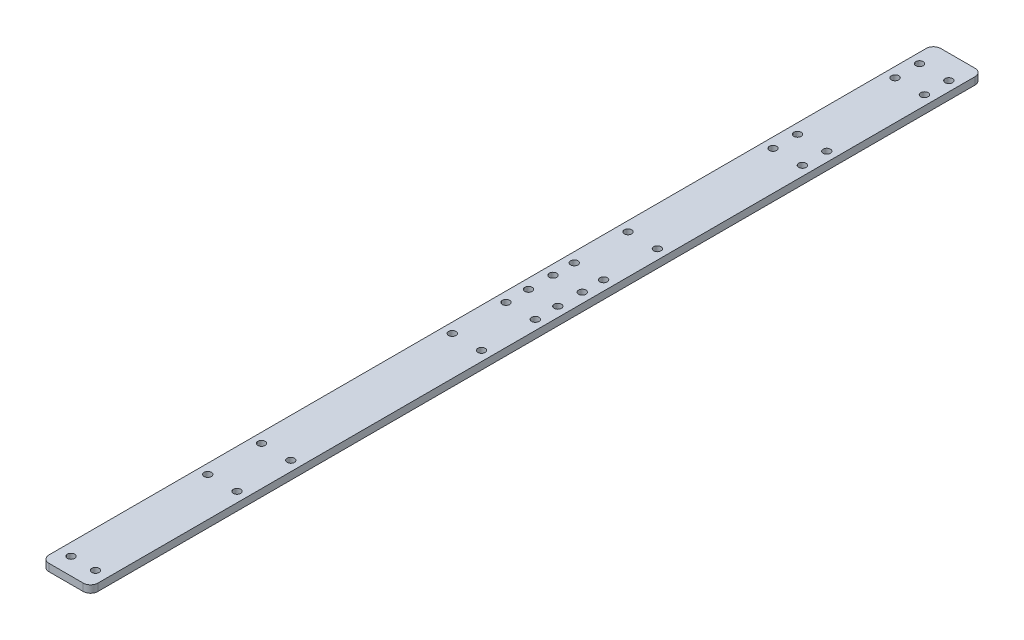
SolidWorks part; units mm, degrees
material "Thornel Mat VMA"
ref_plane "前视基准面" through (0, 0, 0) normal (0, 0, 1) x (1, 0, 0)
ref_plane "上视基准面" through (0, 0, 0) normal (0, 1, 0) x (1, 0, 0)
ref_plane "右视基准面" through (0, 0, 0) normal (1, 0, 0) x (0, 0, -1)
sketch "草图1" plane through (0, 0, 0) normal (0, 1, 0) x (1, 0, 0)
  line L0 (-9.7495, 254.1231) -> (-9.7495, -255.8769)
  line L1 (-9.7495, -255.8769) -> (10.2505, -255.8769)
  line L2 (10.2505, -255.8769) -> (10.2505, 254.1231)
  line L3 (10.2505, 254.1231) -> (-9.7495, 254.1231)
  circle A0 centre (5.2505, -103.8769) radius 1.5
  circle A1 centre (-4.7495, -103.8769) radius 1.5
  circle A2 centre (6.2134, -46.8769) radius 1.5
  circle A3 centre (-5.7866, -46.8769) radius 1.5
  circle A4 centre (6.2134, -24.8769) radius 1.5
  circle A5 centre (-5.7866, -24.8769) radius 1.5
  circle A6 centre (6.2951, 53.1231) radius 1.5
  circle A7 centre (-5.7049, 53.1231) radius 1.5
  circle A8 centre (6.2951, 75.1231) radius 1.5
  circle A9 centre (-5.7049, 75.1231) radius 1.5
  circle A10 centre (6.2634, 84.3731) radius 1.5
  circle A11 centre (-5.7366, 84.3731) radius 1.5
  circle A12 centre (6.2634, 94.3731) radius 1.5
  circle A13 centre (-5.7366, 94.3731) radius 1.5
  circle A14 centre (6.2505, 103.1231) radius 1.5
  circle A15 centre (-5.7495, 103.1231) radius 1.5
  circle A16 centre (6.2505, 125.1231) radius 1.5
  circle A17 centre (-5.7495, 125.1231) radius 1.5
  circle A18 centre (6.3451, 184.3731) radius 1.5
  circle A19 centre (-5.6549, 184.3731) radius 1.5
  circle A20 centre (6.3451, 194.3731) radius 1.5
  circle A21 centre (-5.6549, 194.3731) radius 1.5
  circle A22 centre (6.3005, 234.3731) radius 1.5
  circle A23 centre (-5.6995, 234.3731) radius 1.5
  circle A24 centre (6.3005, 244.3731) radius 1.5
  circle A25 centre (-5.6995, 244.3731) radius 1.5
extrude "凸台-拉伸1" add sketch "草图1" along normal blind 3
sketch "草图2" plane through (0, 3, 0) normal (0, 1, 0) x (1, 0, 0)
  line L0 (10.2505, -255.8769) -> (10.2505, 254.1231) construction
  line L1 (-9.7495, -255.8769) -> (10.2505, -255.8769)
  line L2 (-9.7495, -255.8769) -> (-9.7495, -235.8769)
  line L3 (-9.7495, -235.8769) -> (10.2505, -235.8769)
  line L4 (10.2505, -255.8769) -> (10.2505, -235.8769)
  dimension "D1" = 20
extrude "切除-拉伸1" cut sketch "草图2" against normal through all
sketch "草图3" plane through (0, 3, 0) normal (0, 1, 0) x (1, 0, 0)
  line L0 (0.2505, -235.8769) -> (0.2505, 254.1231) construction
  line L1 (10.2505, -235.8769) -> (-9.7495, -235.8769) construction
  line L2 (10.2505, 254.1231) -> (-9.7495, 254.1231) construction
  line L4 (-5.7495, -200.8769) -> (6.2505, -200.8769) construction
  line L5 (-5.7495, -200.8769) -> (-5.7495, -170.8769) construction
  line L6 (-5.7495, -170.8769) -> (6.2505, -170.8769) construction
  line L7 (6.2505, -200.8769) -> (6.2505, -170.8769) construction
  line L8 (-5.7495, -200.8769) -> (6.2505, -170.8769) construction
  line L9 (-5.7495, -170.8769) -> (6.2505, -200.8769) construction
  circle A0 centre (-5.7495, -170.8769) radius 1.5
  circle A1 centre (-5.7495, -200.8769) radius 1.5
  circle A2 centre (6.2505, -170.8769) radius 1.5
  circle A3 centre (6.2505, -200.8769) radius 1.5
  point P6 (0.2505, -185.8769)
  dimension "D4" = 3
  dimension "D5" = 3
  dimension "D1" = 12
  dimension "D2" = 30
  dimension "D3" = 50
extrude "切除-拉伸2" cut sketch "草图3" against normal through all
sketch "草图4" plane through (0, 3, 0) normal (0, 1, 0) x (1, 0, 0)
  line L0 (-9.7495, 254.1231) -> (-9.7495, -235.8769) construction
  line L1 (-9.7495, -110.8769) -> (19.226, -110.8769)
  line L2 (-9.7495, -110.8769) -> (-9.7495, -257.7382)
  line L3 (-9.7495, -257.7382) -> (19.226, -257.7382)
  line L4 (19.226, -110.8769) -> (19.226, -257.7382)
  line L5 (10.2505, -235.8769) -> (-9.7495, -235.8769) construction
  dimension "D1" = 125
extrude "切除-拉伸3" cut sketch "草图4" against normal through all
fillet "圆角1" radius 3 4 edges at (10.2505, 1.5, -254.1231) (-9.7495, 1.5, -254.1231) (-9.7495, 1.5, 110.8769) (10.2505, 1.5, 110.8769)
